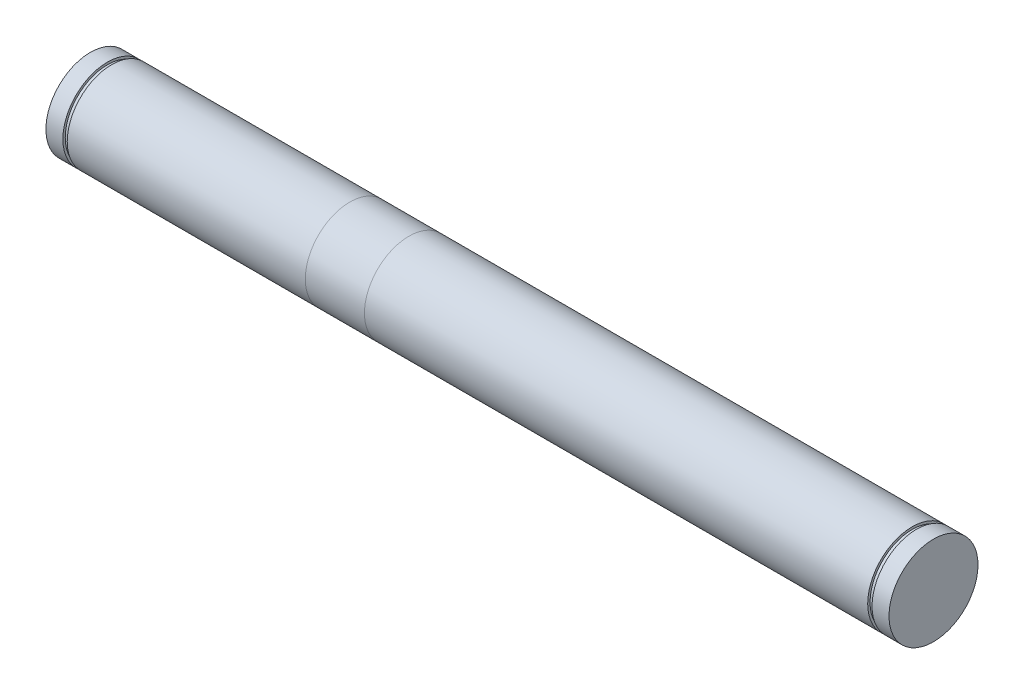
SolidWorks part; units mm, degrees
material "1.7225 (42CrMo4)"
ref_plane "E_Oben" through (0, 0, 0) normal (0, 0, 1) x (1, 0, 0)
ref_plane "E_Vorne" through (0, 0, 0) normal (0, 1, 0) x (1, 0, 0)
ref_plane "E_Rechts" through (0, 0, 0) normal (1, 0, 0) x (0, 0, -1)
ref_axis "A_Drehachse" through (-88.99, 0, 0) along (1, 0, 0)
sketch "Skizze1" plane through (0, 0, 0) normal (0, 0, 1) x (1, 0, 0)
  line L1 (0, -55) -> (0, 55) construction
  line L3 (180, 19) -> (180, 0)
  line L4 (180, 0) -> (-180, 0)
  line L5 (-44, 19.001) -> (-44, 19)
  line L6 (-44, 19.001) -> (-74, 19.001)
  line L7 (-180, 19) -> (-180, 0)
  line L10 (-79, 19) -> (-79, 27)
  line L11 (-79, 27) -> (-74, 27)
  line L12 (-74, 27) -> (-74, 19.001)
  line L14 (-180, 19) -> (-79, 19)
  line L17 (-44, 19) -> (180, 19)
  point P12 (0, 0)
  dimension "D1" = 101
  dimension "D2" = 19
  dimension "D3" = 19.001
  dimension "D4" = 180
  dimension "D5" = 27
  dimension "D6" = 30
  dimension "D7" = 5
revolve "Rotation1" add sketch "Skizze1" angle 360 about L4
sketch "Skizze19" plane through (0, 0, 0) normal (0, 0, 1) x (1, 0, 0)
  line L5 (-88.99, 0) -> (88.99, 0) construction
  line L8 (170.9, 19) -> (172.75, 19)
  line L9 (170.9, 19) -> (170.9, 18)
  line L10 (170.9, 18) -> (172.75, 18)
  line L11 (172.75, 19) -> (172.75, 18)
  line L14 (180, 19) -> (-44, 19) construction
  line L15 (180, -19) -> (180, 19) construction
  dimension "D1" = 7.25
  dimension "D2" = 0
  dimension "D4" = 1.85
  dimension "D5" = 18
revolve "Schnitt-Rotation1" cut sketch "Skizze19" angle 360 about axis through (-88.99, 0, 0) along (1, 0, 0)
sketch "Skizze20" plane through (0, 0, 0) normal (0, 0, 1) x (1, 0, 0)
  line L1 (-172.75, 19) -> (-170.9, 19)
  line L2 (-172.75, 19) -> (-172.75, 18)
  line L3 (-172.75, 18) -> (-170.9, 18)
  line L4 (-170.9, 19) -> (-170.9, 18)
  line L7 (-79, 19) -> (-180, 19) construction
  line L8 (-180, 19) -> (-180, -19) construction
  dimension "D1" = 7.25
  dimension "D2" = 1.85
  dimension "D3" = 1
  dimension "D4" = 0
revolve "Schnitt-Rotation2" cut sketch "Skizze20" angle 360 about axis through (-88.99, 0, 0) along (1, 0, 0)
sketch "Sketch1" plane through (0, 0, 0) normal (0, 0, 1) x (1, 0, 0)
  line L0 (-79, 19) -> (-170.9, 19) construction
  line L1 (-83.331, 19) -> (-69.2296, 19)
  line L2 (-83.331, 19) -> (-83.331, 30.2934)
  line L3 (-83.331, 30.2934) -> (-69.2296, 30.2934)
  line L4 (-69.2296, 19) -> (-69.2296, 30.2934)
  line L5 (-180, 19) -> (-180, -19) construction
  line L6 (-191.1647, 0) -> (203.9937, 0) construction
  dimension "D1" = 14.1014
  dimension "D2" = 11.2934
  dimension "D3" = 110.7704
revolve "Cut-Revolve1" cut sketch "Sketch1" angle 360 about L6
